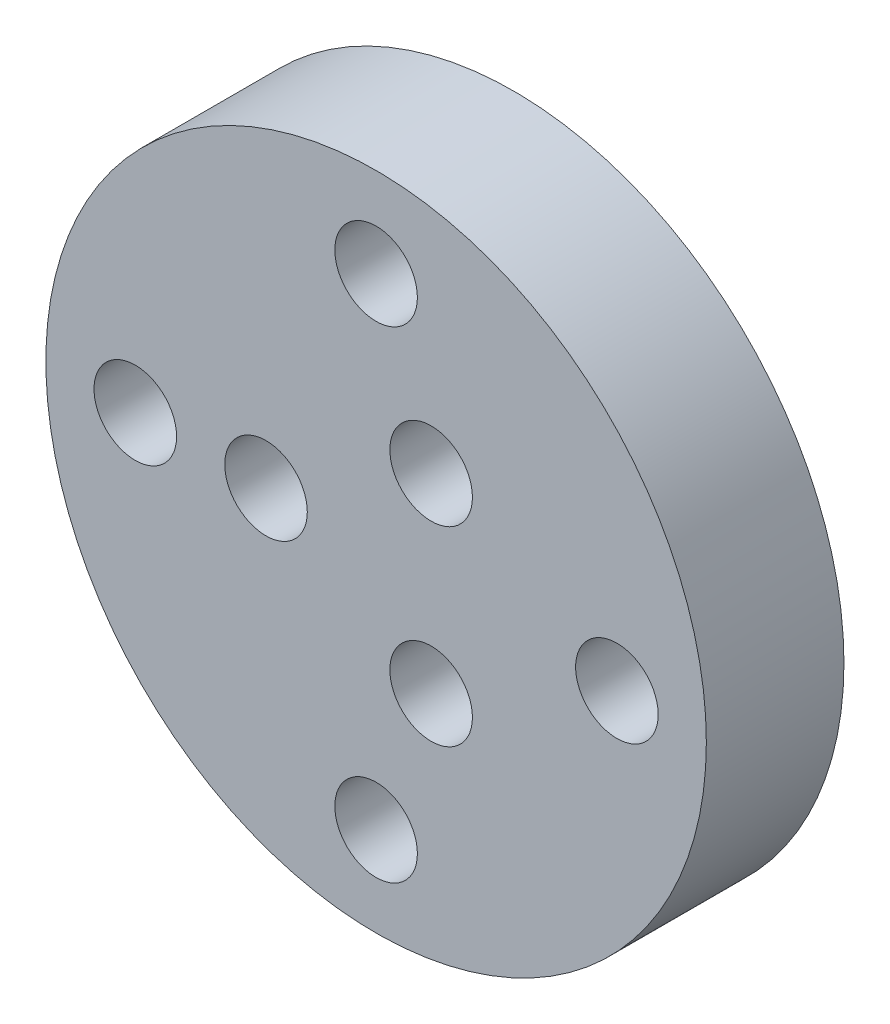
SolidWorks part; units mm, degrees
ref_plane "前视基准面" through (0, 0, 0) normal (0, 0, 1) x (1, 0, 0)
ref_plane "上视基准面" through (0, 0, 0) normal (0, 1, 0) x (1, 0, 0)
ref_plane "右视基准面" through (0, 0, 0) normal (1, 0, 0) x (0, 0, -1)
sketch "草图1" plane through (0, 0, 0) normal (0, 0, 1) x (1, 0, 0)
  circle A0 centre (0, 0) radius 24
  circle A1 centre (0, 0) radius 17.5
  circle A2 centre (0, 0) radius 8
  circle A3 centre (-8, 0) radius 3
  circle A4 centre (4, 6.9282) radius 3
  circle A5 centre (4, -6.9282) radius 3
  circle A6 centre (-17.5, 0) radius 3
  circle A7 centre (0, 17.5) radius 3
  circle A8 centre (17.5, 0) radius 3
  circle A9 centre (0, -17.5) radius 3
  point P13 (0, 0)
  point P23 (0, 0)
  dimension "D1" = 3
  dimension "D2" = 4
extrude "凸台-拉伸1" add sketch "草图1" along normal blind 10 contours A0 A9 A1 A6 A7 A8 | A9 A1 A8 A7 A6 A5 A2 A3 A4 | A5 A2 A4 A3
